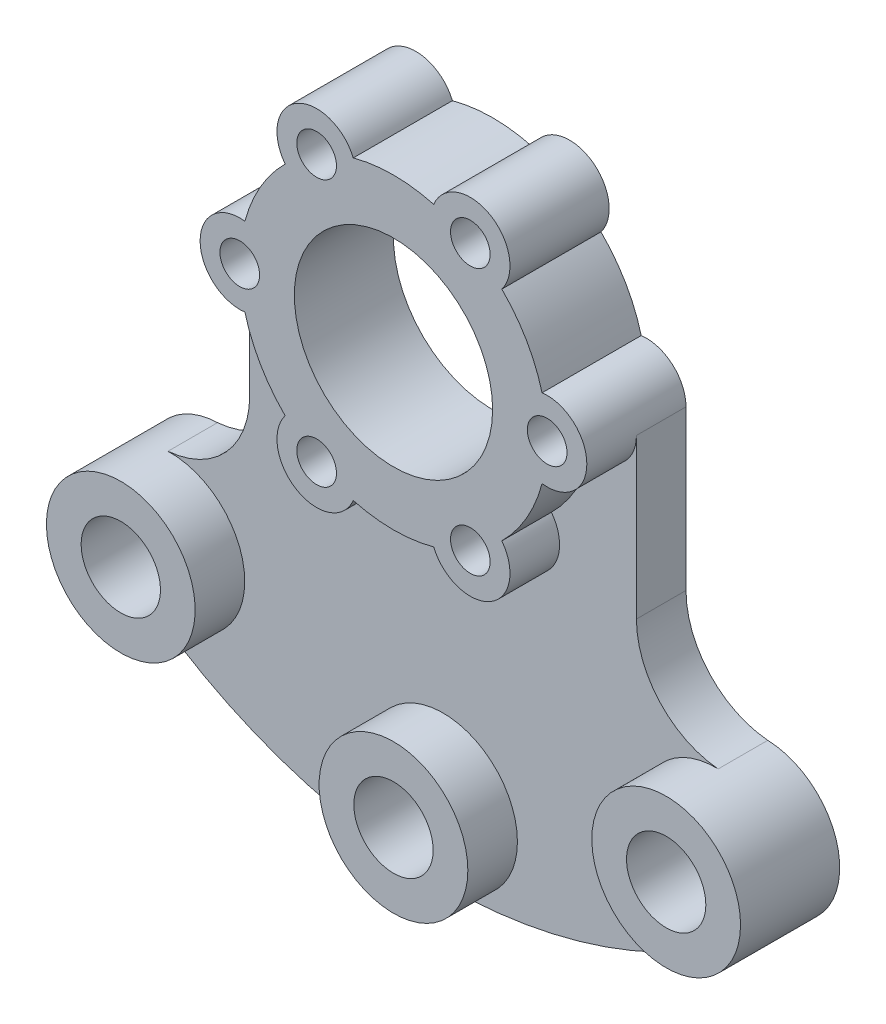
SolidWorks part; units mm, degrees
ref_plane "Alzado" through (0, 0, 0) normal (0, 0, 1) x (1, 0, 0)
ref_plane "Planta" through (0, 0, 0) normal (0, 1, 0) x (1, 0, 0)
ref_plane "Vista lateral" through (0, 0, 0) normal (1, 0, 0) x (0, 0, -1)
sketch "Croquis1" plane through (0, 0, 0) normal (0, 0, 1) x (1, 0, 0)
  line L0 (0, 49.6934) -> (0, -82.97) construction
  line L1 (-48.6605, 0) -> (48.5471, 0) construction
  circle A0 centre (0, 0) radius 20
  arc A1 (-21.8542, 21.9863) -> (-29.9677, 7.9331) centre (0, 0) ccw
  circle A2 centre (31, 0) radius 4
  arc A3 (29.9677, -7.9331) -> (29.9677, 7.9331) centre (31, 0) ccw
  circle A4 centre (15.5, -26.8468) radius 4
  arc A5 (8.1136, -29.9194) -> (21.8542, -21.9863) centre (15.5, -26.8468) ccw
  circle A6 centre (-15.5, -26.8468) radius 4
  arc A7 (-21.8542, -21.9863) -> (-8.1136, -29.9194) centre (-15.5, -26.8468) ccw
  circle A8 centre (-31, 0) radius 4
  arc A9 (-29.9677, 7.9331) -> (-29.9677, -7.9331) centre (-31, 0) ccw
  circle A10 centre (-15.5, 26.8468) radius 4
  arc A11 (-8.1136, 29.9194) -> (-21.8542, 21.9863) centre (-15.5, 26.8468) ccw
  circle A12 centre (15.5, 26.8468) radius 4
  arc A13 (21.8542, 21.9863) -> (8.1136, 29.9194) centre (15.5, 26.8468) ccw
  arc A14 (8.1136, 29.9194) -> (-8.1136, 29.9194) centre (0, 0) ccw
  arc A15 (29.9677, 7.9331) -> (21.8542, 21.9863) centre (0, 0) ccw
  arc A16 (-29.9677, -7.9331) -> (-21.8542, -21.9863) centre (0, 0) ccw
  circle A17 centre (0, -82.97) radius 8
  arc A18 (-8.1136, -29.9194) -> (8.1136, -29.9194) centre (0, 0) ccw
  arc A19 (21.8542, -21.9863) -> (29.9677, -7.9331) centre (0, 0) ccw
  circle A20 centre (0, -82.97) radius 15
  circle A21 centre (55, -65) radius 8
  circle A22 centre (55, -65) radius 15
  circle A23 centre (-55, -65) radius 15
  circle A24 centre (-55, -65) radius 8
  point P29 (0, 0)
  point P41 (0, -97.97)
  dimension "D1" = 40
  dimension "D2" = 8
  dimension "62" = 62
  dimension "D3" = 6
  dimension "16" = 16
  dimension "D4" = 30
  dimension "15" = 16
  dimension "D6" = 16
  dimension "D7" = 65
  dimension "30" = 30
  dimension "D5" = 110
  dimension "D8" = 97.97
extrude "Saliente-Extruir1" add sketch "Croquis1" along normal blind 20
sketch "Croquis2" plane through (0, 0, 0) normal (0, 0, 1) x (1, 0, 0)
  line L1 (-39, 0) -> (-39, -32.0715)
  line L2 (0, 0) -> (0, -74.97) construction
  line L3 (39, 0) -> (39, -32.0715)
  arc A1 (57.4935, -79.7913) -> (-57.4935, -79.7913) centre (0, 2.0286) cw
  circle A2 centre (-55, -65) radius 15 construction
  arc A5 (29.9677, -7.9331) -> (29.9677, 7.9331) centre (31, 0) ccw construction
  circle A6 centre (55, -65) radius 15 construction
  arc A8 (-29.9677, -7.9331) -> (-21.8542, -21.9863) centre (0, 0) ccw
  arc A9 (-56.3285, -50.0589) -> (-57.4935, -79.7913) centre (-55, -65) ccw
  arc A10 (-39, 0) -> (-29.9677, -7.9331) centre (-31, 0) ccw
  arc A11 (-8.1136, -29.9194) -> (-21.8542, -21.9863) centre (-15.5, -26.8468) cw
  arc A12 (8.1136, -29.9194) -> (21.8542, -21.9863) centre (15.5, -26.8468) ccw
  arc A13 (29.9677, -7.9331) -> (39, 0) centre (31, 0) ccw
  arc A14 (-8.1136, -29.9194) -> (8.1136, -29.9194) centre (0, 0) ccw
  arc A15 (21.8542, -21.9863) -> (29.9677, -7.9331) centre (0, 0) ccw
  arc A18 (-56.3285, -50.0589) -> (-39, -32.0715) centre (-57, -32.0715) ccw
  arc A19 (56.3285, -50.0589) -> (57.4935, -79.7913) centre (55, -65) cw
  arc A20 (56.3285, -50.0589) -> (39, -32.0715) centre (57, -32.0715) cw
  circle A21 centre (0, -82.97) radius 8 construction
  point P45 (0, -97.9714)
  dimension "D1" = 36
  dimension "D2" = 100
extrude "Saliente-Extruir2" add sketch "Croquis2" along normal blind 10
sketch "Croquis3" plane through (0, 0, 10) normal (0, 0, 1) x (1, 0, 0)
  circle A0 centre (-55, -65) radius 8
  circle A1 centre (0, -82.97) radius 8
  circle A2 centre (55, -65) radius 8
extrude "Cortar-Extruir1" cut sketch "Croquis3" against normal blind 10
